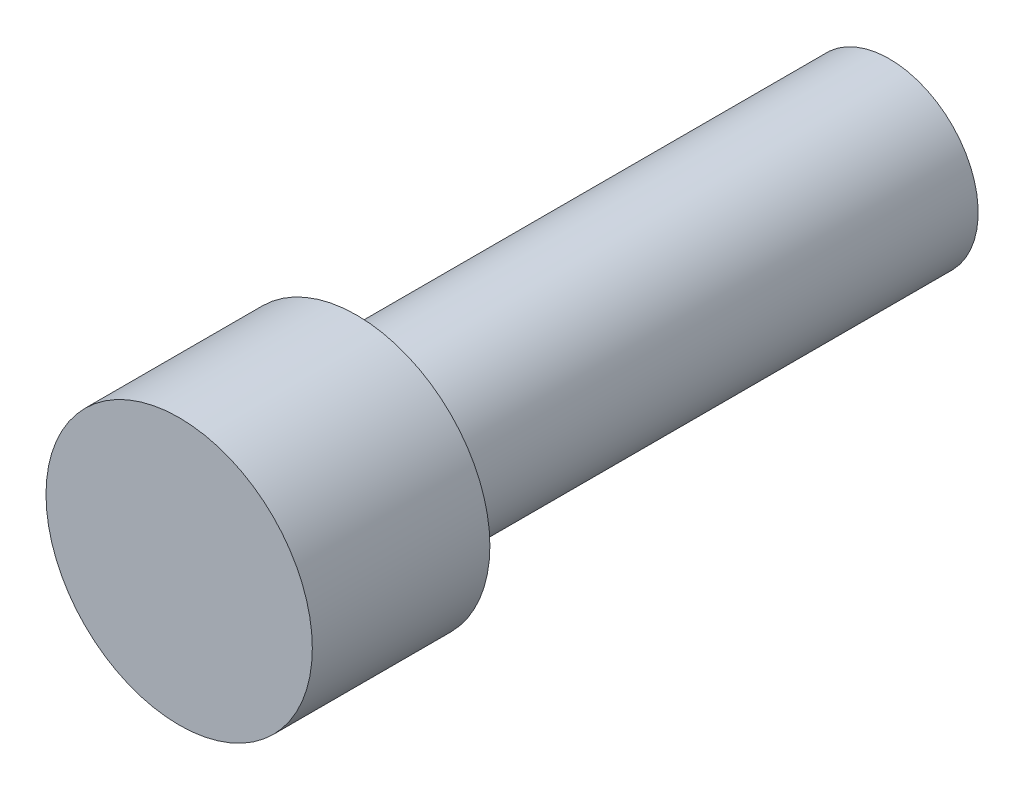
SolidWorks part; units mm, degrees
ref_plane "前视基准面" through (0, 0, 0) normal (0, 0, 1) x (1, 0, 0)
ref_plane "上视基准面" through (0, 0, 0) normal (0, 1, 0) x (1, 0, 0)
ref_plane "右视基准面" through (0, 0, 0) normal (1, 0, 0) x (0, 0, -1)
sketch "草图1" plane through (0, 0, 0) normal (0, 0, 1) x (1, 0, 0)
  circle A0 centre (0, 0) radius 1.5
  dimension "D1" = 3
extrude "凸台-拉伸1" add sketch "草图1" along normal blind 2
sketch "草图2" plane through (0, 0, 0) normal (0, 0, -1) x (-1, 0, 0)
  circle A0 centre (0, 0) radius 1
  dimension "D1" = 2
extrude "凸台-拉伸3" add sketch "草图2" along normal blind 6
